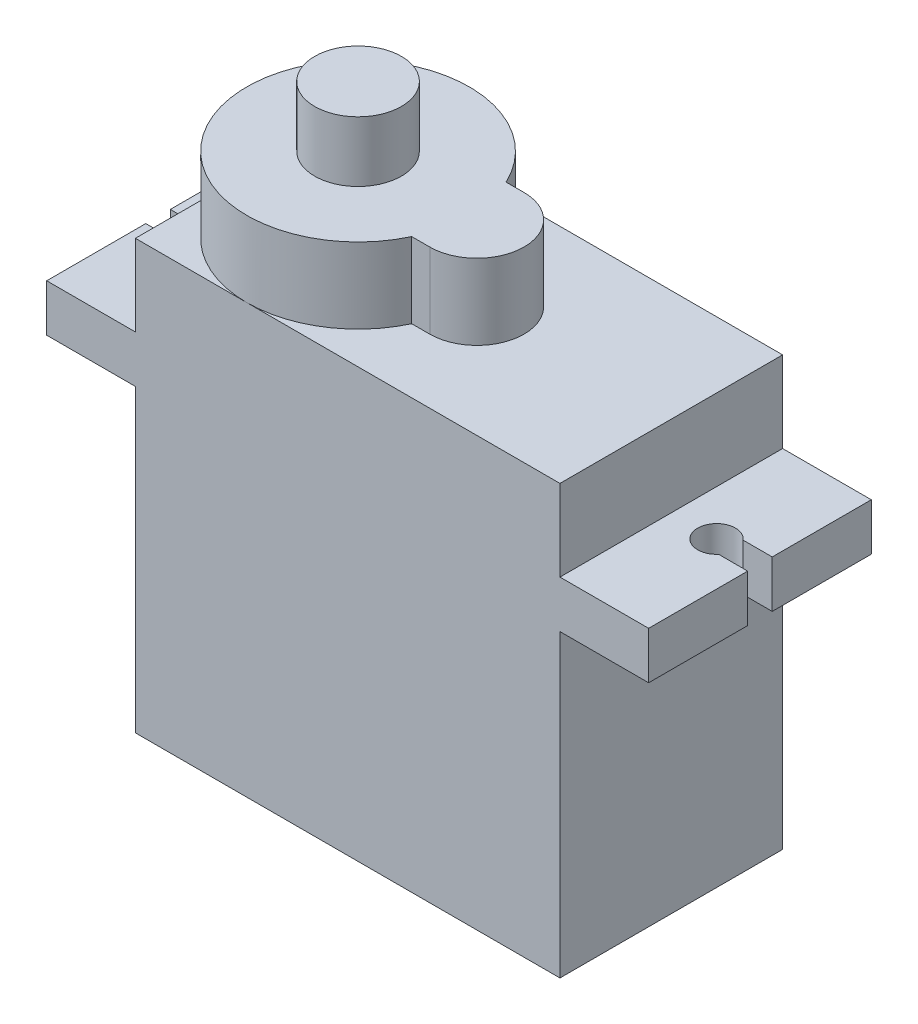
SolidWorks part; units mm, degrees
material "ABS"
ref_plane "Спереди" through (0, 0, 0) normal (0, 0, 1) x (1, 0, 0)
ref_plane "Сверху" through (0, 0, 0) normal (0, 1, 0) x (1, 0, 0)
ref_plane "Справа" through (0, 0, 0) normal (1, 0, 0) x (0, 0, -1)
sketch "Sketch1" plane through (0, 0, 0) normal (0, 0, 1) x (1, 0, 0)
  line L0 (-11.25, 0) -> (11.25, 0)
  line L1 (11.25, 0) -> (11.25, 15.9)
  line L2 (11.25, 15.9) -> (15.95, 15.9)
  line L3 (15.95, 15.9) -> (15.95, 18.4)
  line L4 (15.95, 18.4) -> (11.25, 18.4)
  line L5 (11.25, 18.4) -> (11.25, 22.7)
  line L6 (11.25, 22.7) -> (-11.25, 22.7)
  line L7 (0, 22.7) -> (0, 0) construction
  line L8 (-11.25, 18.4) -> (-11.25, 22.7)
  line L9 (-15.95, 18.4) -> (-11.25, 18.4)
  line L10 (-15.95, 15.9) -> (-15.95, 18.4)
  line L11 (-11.25, 15.9) -> (-15.95, 15.9)
  line L12 (-11.25, 0) -> (-11.25, 15.9)
  dimension "D1" = 22.5
  dimension "D2" = 4.7
  dimension "D3" = 15.9
  dimension "D4" = 2.5
  dimension "D5" = 22.7
extrude "Boss-Extrude1" add sketch "Sketch1" along normal blind 11.8
sketch "Sketch2" plane through (0, 22.7, 0) normal (0, 1, 0) x (1, 0, 0)
  line L0 (-11.25, -5.9) -> (11.25, -5.9) construction
  line L1 (-11.25, -11.8) -> (-11.25, 0) construction
  line L2 (11.25, -11.8) -> (11.25, 0) construction
  line L3 (0.95, -8.4) -> (-0.0058, -8.4)
  line L4 (0.95, -3.4) -> (-0.0058, -3.4)
  arc A0 (-0.0058, -3.4) -> (-0.0058, -8.4) centre (-5.35, -5.9) ccw
  arc A1 (0.95, -8.4) -> (0.95, -3.4) centre (0.95, -5.9) ccw
  dimension "D1" = 11.8
  dimension "D2" = 5
  dimension "D3" = 7.8
extrude "Boss-Extrude2" add sketch "Sketch2" along normal blind 4
sketch "Sketch3" plane through (0, 22.7, 0) normal (0, 1, 0) x (1, 0, 0)
  line L0 (0, 0) -> (0, -11.8) construction
  line L1 (11.25, -11.8) -> (-5.35, -11.8) construction
  line L2 (15.95, -5.9) -> (-15.95, -5.9) construction
  line L3 (15.95, -11.8) -> (15.95, 0) construction
  line L4 (-15.95, -11.8) -> (-15.95, 0) construction
  line L5 (-15.95, -5.25) -> (-14.4099, -5.25)
  line L6 (-15.95, -6.55) -> (-14.4099, -6.55)
  line L7 (-15.95, -6.55) -> (-15.95, -5.25)
  line L8 (15.95, -6.55) -> (15.95, -5.25)
  line L9 (15.95, -6.55) -> (14.4099, -6.55)
  line L10 (15.95, -5.25) -> (14.4099, -5.25)
  arc A0 (-14.4099, -6.55) -> (-14.4099, -5.25) centre (-13.65, -5.9) ccw
  arc A1 (14.4099, -6.55) -> (14.4099, -5.25) centre (13.65, -5.9) cw
  dimension "D2" = 1
  dimension "D1" = 1.3
  dimension "D3" = 2.3
extrude "Cut-Extrude1" cut sketch "Sketch3" against normal through all
sketch "Sketch4" plane through (0, 26.7, 0) normal (0, 1, 0) x (1, 0, 0)
  circle A0 centre (-5.35, -5.9) radius 2.3
  arc A1 (-0.0058, -3.4) -> (-5.35, 0) centre (-5.35, -5.9) ccw construction
  dimension "D1" = 4.6
extrude "Boss-Extrude4" add sketch "Sketch4" along normal blind 3.2
